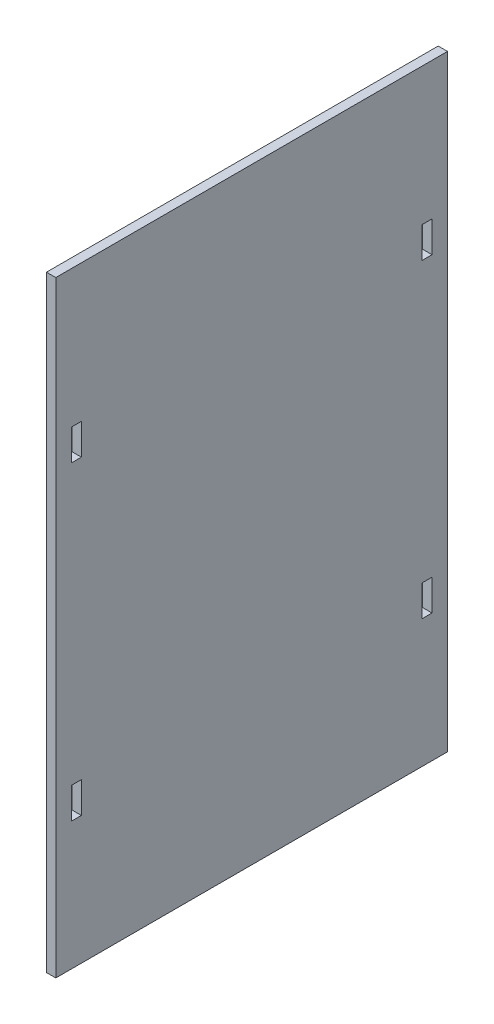
SolidWorks part; units mm, degrees
ref_plane "Front Plane" through (0, 0, 0) normal (0, 0, 1) x (1, 0, 0)
ref_plane "Top Plane" through (0, 0, 0) normal (0, 1, 0) x (1, 0, 0)
ref_plane "Right Plane" through (0, 0, 0) normal (1, 0, 0) x (0, 0, -1)
sketch "Sketch1" plane through (0, 0, 0) normal (1, 0, 0) x (0, 0, -1)
  line L0 (0, 0) -> (252.5, 0)
  line L2 (252.5, 391) -> (0, 391)
  line L5 (10, 282.5) -> (16.5, 282.5)
  line L6 (16.5, 282.5) -> (16.5, 302.5)
  line L7 (16.5, 302.5) -> (10, 302.5)
  line L8 (242.5, 302.5) -> (236, 302.5)
  line L10 (236, 302.5) -> (236, 282.5)
  line L11 (236, 282.5) -> (242.5, 282.5)
  line L12 (242.5, 102.5) -> (236, 102.5)
  line L14 (236, 102.5) -> (236, 82.5)
  line L15 (236, 82.5) -> (242.5, 82.5)
  line L16 (16.5, 102.5) -> (10, 102.5)
  line L17 (16.5, 82.5) -> (16.5, 102.5)
  line L19 (10, 82.5) -> (16.5, 82.5)
  line L26 (0, 391) -> (0, 0)
  line L27 (242.5, 282.5) -> (242.5, 302.5) [skipped]
  line L28 (242.5, 82.5) -> (242.5, 102.5) [skipped]
  line L29 (252.5, 0) -> (252.5, 391)
  line L30 (10, 102.5) -> (10, 82.5)
  line L31 (10, 302.5) -> (10, 282.5)
  line L32 (242.5, 302.5) -> (242.5, 282.5)
  line L33 (242.5, 102.5) -> (242.5, 82.5)
  dimension "D1" = 391
  dimension "D2" = 252.5
  dimension "D3" = 6.5
  dimension "D4" = 20
  dimension "D5" = 88.5
  dimension "D6" = 10
  dimension "D9" = 10
  dimension "D10" = 200
  dimension "D7" = 2
  dimension "D8" = 2
extrude "Boss-Extrude1" add sketch "Sketch1" along normal blind 6
